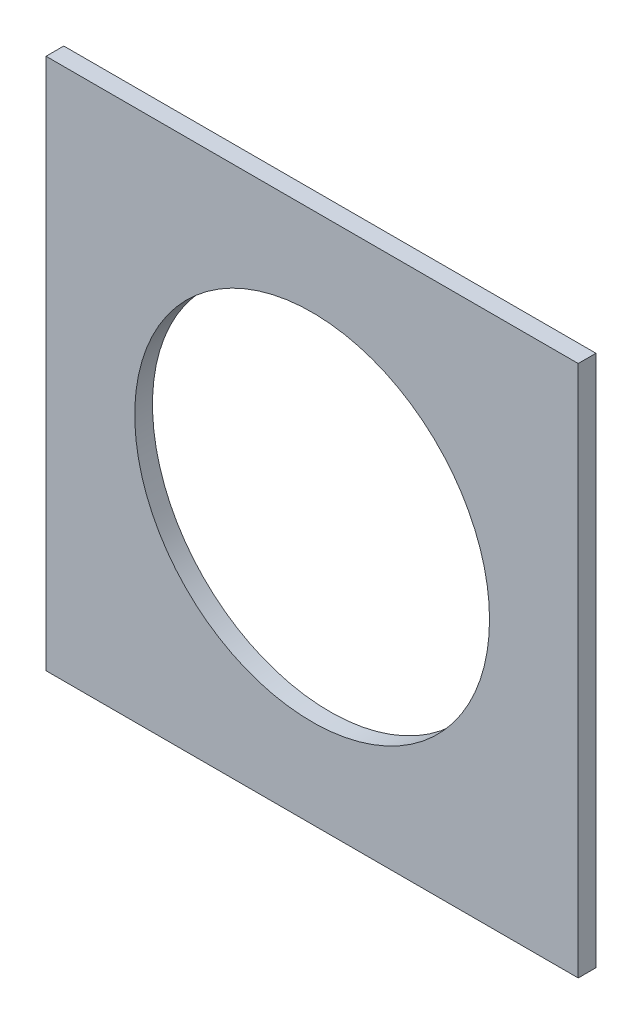
SolidWorks part; units mm, degrees
ref_plane "Front Plane" through (0, 0, 0) normal (0, 0, 1) x (1, 0, 0)
ref_plane "Top Plane" through (0, 0, 0) normal (0, 1, 0) x (1, 0, 0)
ref_plane "Right Plane" through (0, 0, 0) normal (1, 0, 0) x (0, 0, -1)
sketch "Sketch1" plane through (0, 0, 0) normal (0, 0, 1) x (1, 0, 0)
  line L1 (15, 15) -> (-15, 15)
  line L2 (15, 15) -> (15, -15)
  line L3 (15, -15) -> (-15, -15)
  line L4 (-15, 15) -> (-15, -15)
  line L5 (15, 15) -> (-15, -15) construction
  line L6 (15, -15) -> (-15, 15) construction
  circle A0 centre (0, 0) radius 10
  point P0 (0, 0)
  dimension "D3" = 20
  dimension "D1" = 30
  dimension "D2" = 30
extrude "Boss-Extrude1" add sketch "Sketch1" along normal blind 1
